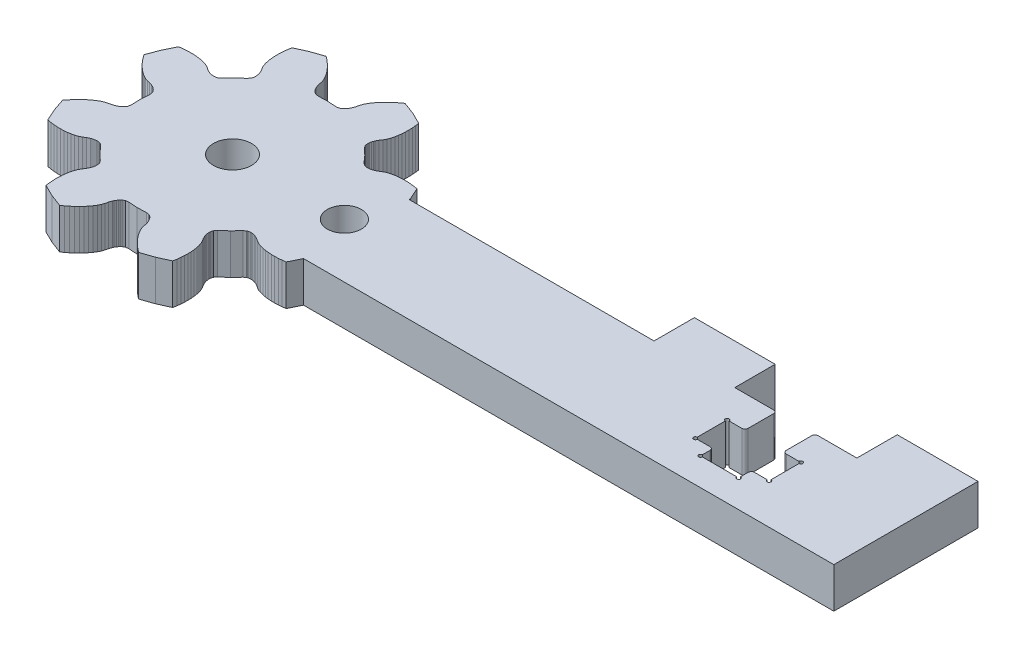
SolidWorks part; units mm, degrees
ref_plane "Front Plane" through (0, 0, 0) normal (0, 0, 1) x (1, 0, 0)
ref_plane "Top Plane" through (0, 0, 0) normal (0, 1, 0) x (1, 0, 0)
ref_plane "Right Plane" through (0, 0, 0) normal (1, 0, 0) x (0, 0, -1)
sketch "Sketch1" plane through (0, 0, 0) normal (0, 1, 0) x (1, 0, 0)
  line L0 (118.5341, 166.0961) -> (137.7907, 166.0961)
  line L1 (160.0907, 166.0961) -> (160.0907, 157.9324)
  line L2 (160.0907, 157.9324) -> (118.4045, 157.9258)
  line L3 (160.0907, 166.0961) -> (160.0907, 169.2711)
  line L4 (160.0907, 169.2711) -> (153.7407, 169.2711)
  line L5 (153.7407, 169.2711) -> (153.7407, 166.0961)
  line L6 (148.9407, 166.0961) -> (148.9407, 157.9306) construction
  line L7 (144.1407, 166.0961) -> (144.1407, 169.2711)
  line L8 (144.1407, 169.2711) -> (137.7907, 169.2711)
  line L9 (137.7907, 169.2711) -> (137.7907, 166.0961)
  line L10 (144.1407, 166.0961) -> (147.1907, 166.0961)
  line L11 (147.4407, 165.8461) -> (147.4407, 163.8461)
  line L12 (147.1907, 163.5961) -> (146.1907, 163.5961)
  line L13 (146.0407, 163.4461) -> (146.0407, 161.2461)
  line L14 (146.1907, 161.0961) -> (147.1907, 161.0961)
  line L15 (147.4407, 160.8461) -> (147.4407, 160.2461)
  line L16 (147.5907, 160.0961) -> (150.2907, 160.0961)
  line L17 (150.4407, 160.8461) -> (150.4407, 160.2461)
  line L18 (151.6907, 161.0961) -> (150.6907, 161.0961)
  line L19 (151.8407, 163.4461) -> (151.8407, 161.2461)
  line L20 (150.6907, 163.5961) -> (151.6907, 163.5961)
  line L21 (150.4407, 165.8461) -> (150.4407, 163.8461)
  line L22 (150.6907, 166.0961) -> (153.7407, 166.0961)
  line L1608 (118.5341, 166.0961) -> (118.5341, 166.193)
  line L1609 (118.5341, 166.193) -> (118.1081, 167.1345)
  line L1610 (118.1081, 167.1345) -> (117.8266, 167.1811)
  line L1611 (117.8266, 167.1811) -> (117.5494, 167.2141)
  line L1612 (117.5494, 167.2141) -> (117.277, 167.2336)
  line L1613 (117.277, 167.2336) -> (117.0101, 167.2392)
  line L1614 (117.0101, 167.2392) -> (116.7493, 167.2309)
  line L1615 (116.7493, 167.2309) -> (116.4956, 167.2082)
  line L1616 (116.4956, 167.2082) -> (116.2497, 167.1704)
  line L1617 (116.2497, 167.1704) -> (116.0133, 167.1164)
  line L1618 (116.0133, 167.1164) -> (115.7883, 167.0435)
  line L1619 (115.7883, 167.0435) -> (115.5824, 166.9415)
  line L1620 (115.5824, 166.9415) -> (115.3904, 166.8184)
  line L1621 (115.3904, 166.8184) -> (115.1836, 166.7174)
  line L1622 (115.1836, 166.7174) -> (115.0732, 166.6772)
  line L1623 (115.0732, 166.6772) -> (114.9567, 166.6456)
  line L1624 (114.9567, 166.6456) -> (114.8323, 166.6253)
  line L1625 (114.8323, 166.6253) -> (114.766, 166.6206)
  line L1626 (114.766, 166.6206) -> (114.696, 166.6208)
  line L1627 (114.696, 166.6208) -> (114.6211, 166.6276)
  line L1628 (114.6211, 166.6276) -> (114.5385, 166.6443)
  line L1629 (114.5385, 166.6443) -> (114.4416, 166.6792)
  line L1630 (114.4416, 166.6792) -> (114.2616, 166.8186)
  line L1631 (114.2616, 166.8186) -> (113.7953, 167.3484)
  line L1632 (113.7953, 167.3484) -> (113.2804, 167.8311)
  line L1633 (113.2804, 167.8311) -> (113.1468, 168.0154)
  line L1634 (113.1468, 168.0154) -> (113.1149, 168.1133)
  line L1635 (113.1149, 168.1133) -> (113.1008, 168.1964)
  line L1636 (113.1008, 168.1964) -> (113.0963, 168.2716)
  line L1637 (113.0963, 168.2716) -> (113.0983, 168.3415)
  line L1638 (113.0983, 168.3415) -> (113.1051, 168.4076)
  line L1639 (113.1051, 168.4076) -> (113.1293, 168.5313)
  line L1640 (113.1293, 168.5313) -> (113.1645, 168.6468)
  line L1641 (113.1645, 168.6468) -> (113.2082, 168.7559)
  line L1642 (113.2082, 168.7559) -> (113.3157, 168.9594)
  line L1643 (113.3157, 168.9594) -> (113.4447, 169.1474)
  line L1644 (113.4447, 169.1474) -> (113.5532, 169.35)
  line L1645 (113.5532, 169.35) -> (113.633, 169.5726)
  line L1646 (113.633, 169.5726) -> (113.6945, 169.8072)
  line L1647 (113.6945, 169.8072) -> (113.74, 170.0517)
  line L1648 (113.74, 170.0517) -> (113.7706, 170.3047)
  line L1649 (113.7706, 170.3047) -> (113.7871, 170.565)
  line L1650 (113.7871, 170.565) -> (113.7899, 170.832)
  line L1651 (113.7899, 170.832) -> (113.779, 171.1049)
  line L1652 (113.779, 171.1049) -> (113.7547, 171.383)
  line L1653 (113.7547, 171.383) -> (113.717, 171.6658)
  line L1654 (113.717, 171.6658) -> (112.7893, 172.1212)
  line L1655 (112.7893, 172.1212) -> (111.8223, 172.4857)
  line L1656 (111.8223, 172.4857) -> (111.5903, 172.3196)
  line L1657 (111.5903, 172.3196) -> (111.371, 172.1469)
  line L1658 (111.371, 172.1469) -> (111.1646, 171.9681)
  line L1659 (111.1646, 171.9681) -> (110.9718, 171.7833)
  line L1660 (110.9718, 171.7833) -> (110.7934, 171.593)
  line L1661 (110.7934, 171.593) -> (110.63, 171.3975)
  line L1662 (110.63, 171.3975) -> (110.4829, 171.197)
  line L1663 (110.4829, 171.197) -> (110.3539, 170.9916)
  line L1664 (110.3539, 170.9916) -> (110.2464, 170.781)
  line L1665 (110.2464, 170.781) -> (110.1728, 170.5633)
  line L1666 (110.1728, 170.5633) -> (110.1241, 170.3405)
  line L1667 (110.1241, 170.3405) -> (110.0493, 170.1228)
  line L1668 (110.0493, 170.1228) -> (109.9997, 170.0163)
  line L1669 (109.9997, 170.0163) -> (109.9397, 169.9116)
  line L1670 (109.9397, 169.9116) -> (109.8661, 169.8092)
  line L1671 (109.8661, 169.8092) -> (109.8225, 169.759)
  line L1672 (109.8225, 169.759) -> (109.7729, 169.7097)
  line L1673 (109.7729, 169.7097) -> (109.715, 169.6615)
  line L1674 (109.715, 169.6615) -> (109.6448, 169.615)
  line L1675 (109.6448, 169.615) -> (109.5516, 169.5712)
  line L1676 (109.5516, 169.5712) -> (109.3258, 169.5424)
  line L1677 (109.3258, 169.5424) -> (108.6215, 169.5873)
  line L1678 (108.6215, 169.5873) -> (107.9161, 169.5646)
  line L1679 (107.9161, 169.5646) -> (107.6912, 169.6004)
  line L1680 (107.6912, 169.6004) -> (107.5995, 169.6471)
  line L1681 (107.5995, 169.6471) -> (107.5307, 169.6959)
  line L1682 (107.5307, 169.6959) -> (107.4745, 169.7459)
  line L1683 (107.4745, 169.7459) -> (107.4264, 169.7967)
  line L1684 (107.4264, 169.7967) -> (107.3844, 169.8482)
  line L1685 (107.3844, 169.8482) -> (107.3141, 169.9529)
  line L1686 (107.3141, 169.9529) -> (107.2574, 170.0594)
  line L1687 (107.2574, 170.0594) -> (107.2111, 170.1674)
  line L1688 (107.2111, 170.1674) -> (107.1432, 170.3873)
  line L1689 (107.1432, 170.3873) -> (107.1015, 170.6115)
  line L1690 (107.1015, 170.6115) -> (107.0349, 170.8315)
  line L1691 (107.0349, 170.8315) -> (106.934, 171.0453)
  line L1692 (106.934, 171.0453) -> (106.8116, 171.2547)
  line L1693 (106.8116, 171.2547) -> (106.6708, 171.4597)
  line L1694 (106.6708, 171.4597) -> (106.5136, 171.6603)
  line L1695 (106.5136, 171.6603) -> (106.3412, 171.856)
  line L1696 (106.3412, 171.856) -> (106.1543, 172.0467)
  line L1697 (106.1543, 172.0467) -> (105.9537, 172.232)
  line L1698 (105.9537, 172.232) -> (105.7399, 172.4115)
  line L1699 (105.7399, 172.4115) -> (105.5133, 172.5848)
  line L1700 (105.5133, 172.5848) -> (104.5353, 172.2508)
  line L1701 (104.5353, 172.2508) -> (103.5937, 171.8248)
  line L1702 (103.5937, 171.8248) -> (103.5472, 171.5433)
  line L1703 (103.5472, 171.5433) -> (103.5141, 171.2661)
  line L1704 (103.5141, 171.2661) -> (103.4947, 170.9937)
  line L1705 (103.4947, 170.9937) -> (103.489, 170.7268)
  line L1706 (103.489, 170.7268) -> (103.4974, 170.4661)
  line L1707 (103.4974, 170.4661) -> (103.52, 170.2122)
  line L1708 (103.52, 170.2122) -> (103.5578, 169.9665)
  line L1709 (103.5578, 169.9665) -> (103.6119, 169.73)
  line L1710 (103.6119, 169.73) -> (103.6847, 169.5051)
  line L1711 (103.6847, 169.5051) -> (103.7867, 169.2991)
  line L1712 (103.7867, 169.2991) -> (103.9099, 169.1071)
  line L1713 (103.9099, 169.1071) -> (104.0108, 168.9003)
  line L1714 (104.0108, 168.9003) -> (104.0511, 168.7899)
  line L1715 (104.0511, 168.7899) -> (104.0826, 168.6735)
  line L1716 (104.0826, 168.6735) -> (104.103, 168.549)
  line L1717 (104.103, 168.549) -> (104.1077, 168.4827)
  line L1718 (104.1077, 168.4827) -> (104.1075, 168.4127)
  line L1719 (104.1075, 168.4127) -> (104.1006, 168.3378)
  line L1720 (104.1006, 168.3378) -> (104.0839, 168.2552)
  line L1721 (104.0839, 168.2552) -> (104.049, 168.1583)
  line L1722 (104.049, 168.1583) -> (103.9096, 167.9783)
  line L1723 (103.9096, 167.9783) -> (103.3799, 167.512)
  line L1724 (103.3799, 167.512) -> (102.8972, 166.9971)
  line L1725 (102.8972, 166.9971) -> (102.7129, 166.8635)
  line L1726 (102.7129, 166.8635) -> (102.6149, 166.8316)
  line L1727 (102.6149, 166.8316) -> (102.5318, 166.8175)
  line L1728 (102.5318, 166.8175) -> (102.4567, 166.8131)
  line L1729 (102.4567, 166.8131) -> (102.3868, 166.815)
  line L1730 (102.3868, 166.815) -> (102.3207, 166.8218)
  line L1731 (102.3207, 166.8218) -> (102.1969, 166.8461)
  line L1732 (102.1969, 166.8461) -> (102.0815, 166.8813)
  line L1733 (102.0815, 166.8813) -> (101.9724, 166.9249)
  line L1734 (101.9724, 166.9249) -> (101.7689, 167.0324)
  line L1735 (101.7689, 167.0324) -> (101.5809, 167.1615)
  line L1736 (101.5809, 167.1615) -> (101.3782, 167.2699)
  line L1737 (101.3782, 167.2699) -> (101.1557, 167.3498)
  line L1738 (101.1557, 167.3498) -> (100.921, 167.4112)
  line L1739 (100.921, 167.4112) -> (100.6765, 167.4567)
  line L1740 (100.6765, 167.4567) -> (100.4236, 167.4874)
  line L1741 (100.4236, 167.4874) -> (100.1632, 167.5039)
  line L1742 (100.1632, 167.5039) -> (99.8963, 167.5066)
  line L1743 (99.8963, 167.5066) -> (99.6234, 167.4957)
  line L1744 (99.6234, 167.4957) -> (99.3453, 167.4714)
  line L1745 (99.3453, 167.4714) -> (99.0625, 167.4337)
  line L1746 (99.0625, 167.4337) -> (98.6071, 166.506)
  line L1747 (98.6071, 166.506) -> (98.2426, 165.539)
  line L1748 (98.2426, 165.539) -> (98.4087, 165.3071)
  line L1749 (98.4087, 165.3071) -> (98.5813, 165.0877)
  line L1750 (98.5813, 165.0877) -> (98.7602, 164.8813)
  line L1751 (98.7602, 164.8813) -> (98.9449, 164.6886)
  line L1752 (98.9449, 164.6886) -> (99.1352, 164.5101)
  line L1753 (99.1352, 164.5101) -> (99.3307, 164.3467)
  line L1754 (99.3307, 164.3467) -> (99.5312, 164.1996)
  line L1755 (99.5312, 164.1996) -> (99.7367, 164.0706)
  line L1756 (99.7367, 164.0706) -> (99.9472, 163.9631)
  line L1757 (99.9472, 163.9631) -> (100.165, 163.8895)
  line L1758 (100.165, 163.8895) -> (100.3878, 163.8409)
  line L1759 (100.3878, 163.8409) -> (100.6054, 163.7661)
  line L1760 (100.6054, 163.7661) -> (100.7119, 163.7165)
  line L1761 (100.7119, 163.7165) -> (100.8166, 163.6564)
  line L1762 (100.8166, 163.6564) -> (100.919, 163.5828)
  line L1763 (100.919, 163.5828) -> (100.9692, 163.5392)
  line L1764 (100.9692, 163.5392) -> (101.0185, 163.4896)
  line L1765 (101.0185, 163.4896) -> (101.0667, 163.4318)
  line L1766 (101.0667, 163.4318) -> (101.1133, 163.3615)
  line L1767 (101.1133, 163.3615) -> (101.1571, 163.2683)
  line L1768 (101.1571, 163.2683) -> (101.1858, 163.0425)
  line L1769 (101.1858, 163.0425) -> (101.1409, 162.3382)
  line L1770 (101.1409, 162.3382) -> (101.1637, 161.6328)
  line L1771 (101.1637, 161.6328) -> (101.1279, 161.408)
  line L1772 (101.1279, 161.408) -> (101.0812, 161.3162)
  line L1773 (101.0812, 161.3162) -> (101.0324, 161.2475)
  line L1774 (101.0324, 161.2475) -> (100.9824, 161.1912)
  line L1775 (100.9824, 161.1912) -> (100.9316, 161.1431)
  line L1776 (100.9316, 161.1431) -> (100.88, 161.1012)
  line L1777 (100.88, 161.1012) -> (100.7753, 161.0308)
  line L1778 (100.7753, 161.0308) -> (100.6689, 160.9741)
  line L1779 (100.6689, 160.9741) -> (100.5608, 160.9278)
  line L1780 (100.5608, 160.9278) -> (100.341, 160.8599)
  line L1781 (100.341, 160.8599) -> (100.1167, 160.8183)
  line L1782 (100.1167, 160.8183) -> (99.8968, 160.7516)
  line L1783 (99.8968, 160.7516) -> (99.6829, 160.6507)
  line L1784 (99.6829, 160.6507) -> (99.4736, 160.5283)
  line L1785 (99.4736, 160.5283) -> (99.2685, 160.3876)
  line L1786 (99.2685, 160.3876) -> (99.068, 160.2304)
  line L1787 (99.068, 160.2304) -> (98.8722, 160.0579)
  line L1788 (98.8722, 160.0579) -> (98.6815, 159.8711)
  line L1789 (98.6815, 159.8711) -> (98.4962, 159.6704)
  line L1790 (98.4962, 159.6704) -> (98.3167, 159.4566)
  line L1791 (98.3167, 159.4566) -> (98.1435, 159.23)
  line L1792 (98.1435, 159.23) -> (98.4774, 158.252)
  line L1793 (98.4774, 158.252) -> (98.9034, 157.3104)
  line L1794 (98.9034, 157.3104) -> (99.1849, 157.2639)
  line L1795 (99.1849, 157.2639) -> (99.4621, 157.2308)
  line L1796 (99.4621, 157.2308) -> (99.7345, 157.2114)
  line L1797 (99.7345, 157.2114) -> (100.0015, 157.2058)
  line L1798 (100.0015, 157.2058) -> (100.2622, 157.2141)
  line L1799 (100.2622, 157.2141) -> (100.516, 157.2368)
  line L1800 (100.516, 157.2368) -> (100.7618, 157.2745)
  line L1801 (100.7618, 157.2745) -> (100.9983, 157.3286)
  line L1802 (100.9983, 157.3286) -> (101.2232, 157.4015)
  line L1803 (101.2232, 157.4015) -> (101.4292, 157.5035)
  line L1804 (101.4292, 157.5035) -> (101.6211, 157.6266)
  line L1805 (101.6211, 157.6266) -> (101.8279, 157.7276)
  line L1806 (101.8279, 157.7276) -> (101.9383, 157.7678)
  line L1807 (101.9383, 157.7678) -> (102.0548, 157.7994)
  line L1808 (102.0548, 157.7994) -> (102.1793, 157.8197)
  line L1809 (102.1793, 157.8197) -> (102.2455, 157.8244)
  line L1810 (102.2455, 157.8244) -> (102.3155, 157.8242)
  line L1811 (102.3155, 157.8242) -> (102.3905, 157.8174)
  line L1812 (102.3905, 157.8174) -> (102.4731, 157.8007)
  line L1813 (102.4731, 157.8007) -> (102.5699, 157.7657)
  line L1814 (102.5699, 157.7657) -> (102.7499, 157.6264)
  line L1815 (102.7499, 157.6264) -> (103.2163, 157.0966)
  line L1816 (103.2163, 157.0966) -> (103.7311, 156.6139)
  line L1817 (103.7311, 156.6139) -> (103.8648, 156.4296)
  line L1818 (103.8648, 156.4296) -> (103.8966, 156.3317)
  line L1819 (103.8966, 156.3317) -> (103.9107, 156.2486)
  line L1820 (103.9107, 156.2486) -> (103.9152, 156.1734)
  line L1821 (103.9152, 156.1734) -> (103.9132, 156.1035)
  line L1822 (103.9132, 156.1035) -> (103.9065, 156.0374)
  line L1823 (103.9065, 156.0374) -> (103.8822, 155.9136)
  line L1824 (103.8822, 155.9136) -> (103.847, 155.7982)
  line L1825 (103.847, 155.7982) -> (103.8033, 155.6891)
  line L1826 (103.8033, 155.6891) -> (103.6959, 155.4856)
  line L1827 (103.6959, 155.4856) -> (103.5668, 155.2976)
  line L1828 (103.5668, 155.2976) -> (103.4584, 155.0949)
  line L1829 (103.4584, 155.0949) -> (103.3785, 154.8724)
  line L1830 (103.3785, 154.8724) -> (103.317, 154.6378)
  line L1831 (103.317, 154.6378) -> (103.2715, 154.3933)
  line L1832 (103.2715, 154.3933) -> (103.2409, 154.1403)
  line L1833 (103.2409, 154.1403) -> (103.2244, 153.8799)
  line L1834 (103.2244, 153.8799) -> (103.2217, 153.613)
  line L1835 (103.2217, 153.613) -> (103.2325, 153.3401)
  line L1836 (103.2325, 153.3401) -> (103.2568, 153.062)
  line L1837 (103.2568, 153.062) -> (103.2945, 152.7792)
  line L1838 (103.2945, 152.7792) -> (104.2222, 152.3238)
  line L1839 (104.2222, 152.3238) -> (105.1892, 151.9593)
  line L1840 (105.1892, 151.9593) -> (105.4212, 152.1254)
  line L1841 (105.4212, 152.1254) -> (105.6406, 152.298)
  line L1842 (105.6406, 152.298) -> (105.8469, 152.4769)
  line L1843 (105.8469, 152.4769) -> (106.0397, 152.6617)
  line L1844 (106.0397, 152.6617) -> (106.2182, 152.8519)
  line L1845 (106.2182, 152.8519) -> (106.3816, 153.0474)
  line L1846 (106.3816, 153.0474) -> (106.5287, 153.248)
  line L1847 (106.5287, 153.248) -> (106.6576, 153.4534)
  line L1848 (106.6576, 153.4534) -> (106.7652, 153.6639)
  line L1849 (106.7652, 153.6639) -> (106.8387, 153.8817)
  line L1850 (106.8387, 153.8817) -> (106.8874, 154.1045)
  line L1851 (106.8874, 154.1045) -> (106.9622, 154.3221)
  line L1852 (106.9622, 154.3221) -> (107.0118, 154.4286)
  line L1853 (107.0118, 154.4286) -> (107.0719, 154.5333)
  line L1854 (107.0719, 154.5333) -> (107.1455, 154.6358)
  line L1855 (107.1455, 154.6358) -> (107.189, 154.6859)
  line L1856 (107.189, 154.6859) -> (107.2386, 154.7352)
  line L1857 (107.2386, 154.7352) -> (107.2965, 154.7834)
  line L1858 (107.2965, 154.7834) -> (107.3667, 154.83)
  line L1859 (107.3667, 154.83) -> (107.4599, 154.8738)
  line L1860 (107.4599, 154.8738) -> (107.6857, 154.9026)
  line L1861 (107.6857, 154.9026) -> (108.3901, 154.8577)
  line L1862 (108.3901, 154.8577) -> (109.0955, 154.8804)
  line L1863 (109.0955, 154.8804) -> (109.3203, 154.8446)
  line L1864 (109.3203, 154.8446) -> (109.4121, 154.7979)
  line L1865 (109.4121, 154.7979) -> (109.4808, 154.7491)
  line L1866 (109.4808, 154.7491) -> (109.5371, 154.6991)
  line L1867 (109.5371, 154.6991) -> (109.5851, 154.6483)
  line L1868 (109.5851, 154.6483) -> (109.6271, 154.5968)
  line L1869 (109.6271, 154.5968) -> (109.6974, 154.4921)
  line L1870 (109.6974, 154.4921) -> (109.7542, 154.3856)
  line L1871 (109.7542, 154.3856) -> (109.8004, 154.2775)
  line L1872 (109.8004, 154.2775) -> (109.8684, 154.0577)
  line L1873 (109.8684, 154.0577) -> (109.91, 153.8335)
  line L1874 (109.91, 153.8335) -> (109.9767, 153.6135)
  line L1875 (109.9767, 153.6135) -> (110.0775, 153.3997)
  line L1876 (110.0775, 153.3997) -> (110.2, 153.1903)
  line L1877 (110.2, 153.1903) -> (110.3407, 152.9852)
  line L1878 (110.3407, 152.9852) -> (110.4979, 152.7847)
  line L1879 (110.4979, 152.7847) -> (110.6703, 152.5889)
  line L1880 (110.6703, 152.5889) -> (110.8572, 152.3982)
  line L1881 (110.8572, 152.3982) -> (111.0578, 152.213)
  line L1882 (111.0578, 152.213) -> (111.2717, 152.0335)
  line L1883 (111.2717, 152.0335) -> (111.4983, 151.8602)
  line L1884 (111.4983, 151.8602) -> (112.4763, 152.1941)
  line L1885 (112.4763, 152.1941) -> (113.4178, 152.6202)
  line L1886 (113.4178, 152.6202) -> (113.4644, 152.9016)
  line L1887 (113.4644, 152.9016) -> (113.4974, 153.1789)
  line L1888 (113.4974, 153.1789) -> (113.5168, 153.4513)
  line L1889 (113.5168, 153.4513) -> (113.5225, 153.7182)
  line L1890 (113.5225, 153.7182) -> (113.5142, 153.9789)
  line L1891 (113.5142, 153.9789) -> (113.4915, 154.2327)
  line L1892 (113.4915, 154.2327) -> (113.4537, 154.4785)
  line L1893 (113.4537, 154.4785) -> (113.3996, 154.715)
  line L1894 (113.3996, 154.715) -> (113.3268, 154.9399)
  line L1895 (113.3268, 154.9399) -> (113.2248, 155.1459)
  line L1896 (113.2248, 155.1459) -> (113.1017, 155.3378)
  line L1897 (113.1017, 155.3378) -> (113.0007, 155.5446)
  line L1898 (113.0007, 155.5446) -> (112.9604, 155.655)
  line L1899 (112.9604, 155.655) -> (112.9289, 155.7715)
  line L1900 (112.9289, 155.7715) -> (112.9085, 155.896)
  line L1901 (112.9085, 155.896) -> (112.9038, 155.9623)
  line L1902 (112.9038, 155.9623) -> (112.9041, 156.0322)
  line L1903 (112.9041, 156.0322) -> (112.9109, 156.1072)
  line L1904 (112.9109, 156.1072) -> (112.9276, 156.1898)
  line L1905 (112.9276, 156.1898) -> (112.9625, 156.2866)
  line L1906 (112.9625, 156.2866) -> (113.1019, 156.4667)
  line L1907 (113.1019, 156.4667) -> (113.6316, 156.933)
  line L1908 (113.6316, 156.933) -> (114.1144, 157.4478)
  line L1909 (114.1144, 157.4478) -> (114.2987, 157.5815)
  line L1910 (114.2987, 157.5815) -> (114.3966, 157.6133)
  line L1911 (114.3966, 157.6133) -> (114.4797, 157.6275)
  line L1912 (114.4797, 157.6275) -> (114.5548, 157.6319)
  line L1913 (114.5548, 157.6319) -> (114.6247, 157.63)
  line L1914 (114.6247, 157.63) -> (114.6908, 157.6232)
  line L1915 (114.6908, 157.6232) -> (114.8146, 157.5989)
  line L1916 (114.8146, 157.5989) -> (114.9301, 157.5637)
  line L1917 (114.9301, 157.5637) -> (115.0392, 157.52)
  line L1918 (115.0392, 157.52) -> (115.2426, 157.4126)
  line L1919 (115.2426, 157.4126) -> (115.4307, 157.2835)
  line L1920 (115.4307, 157.2835) -> (115.6333, 157.1751)
  line L1921 (115.6333, 157.1751) -> (115.8558, 157.0952)
  line L1922 (115.8558, 157.0952) -> (116.0905, 157.0337)
  line L1923 (116.0905, 157.0337) -> (116.335, 156.9883)
  line L1924 (116.335, 156.9883) -> (116.5879, 156.9576)
  line L1925 (116.5879, 156.9576) -> (116.8483, 156.9411)
  line L1926 (116.8483, 156.9411) -> (117.1153, 156.9384)
  line L1927 (117.1153, 156.9384) -> (117.3881, 156.9492)
  line L1928 (117.3881, 156.9492) -> (117.6663, 156.9736)
  line L1929 (117.6663, 156.9736) -> (117.949, 157.0112)
  line L1930 (117.949, 157.0112) -> (118.4045, 157.9389)
  line L1931 (118.4045, 157.9389) -> (118.4045, 157.9258)
  circle A0 centre (108.5161, 162.2225) radius 1.5
  circle A1 centre (117.3319, 162.206) radius 1.3413
  arc A2 (146.0407, 161.2461) -> (146.1907, 161.0961) centre (146.0407, 161.0961) ccw
  arc A3 (146.1907, 163.5961) -> (146.0407, 163.4461) centre (146.0407, 163.5961) ccw
  arc A4 (147.4407, 160.2461) -> (147.5907, 160.0961) centre (147.4407, 160.0961) ccw
  arc A5 (147.1907, 161.0961) -> (147.4407, 160.8461) centre (147.1907, 160.8461) cw
  arc A6 (147.4407, 163.8461) -> (147.1907, 163.5961) centre (147.1907, 163.8461) cw
  arc A7 (150.4407, 163.8461) -> (150.6907, 163.5961) centre (150.6907, 163.8461) ccw
  arc A8 (150.6907, 161.0961) -> (150.4407, 160.8461) centre (150.6907, 160.8461) ccw
  arc A9 (150.4407, 160.2461) -> (150.2907, 160.0961) centre (150.4407, 160.0961) cw
  arc A10 (151.6907, 163.5961) -> (151.8407, 163.4461) centre (151.8407, 163.5961) cw
  arc A11 (151.8407, 161.2461) -> (151.6907, 161.0961) centre (151.8407, 161.0961) cw
  arc A12 (150.4407, 165.8461) -> (150.6907, 166.0961) centre (150.6907, 165.8461) cw
  arc A13 (147.4407, 165.8461) -> (147.1907, 166.0961) centre (147.1907, 165.8461) ccw
  point P30 (147.4407, 161.0961)
  point P33 (147.4407, 163.5961)
  point P49 (148.9407, 160.0961)
  point P50 (150.4407, 163.5961)
  point P51 (150.4407, 161.0961)
  point P54 (150.4407, 166.0961)
  point P57 (147.4407, 166.0961)
  dimension "D12" = 0.3
  dimension "D13" = 0.3
  dimension "D14" = 0.3
  dimension "D15" = 0.25
  dimension "D16" = 0.25
  dimension "D1" = 3.175
  dimension "D2" = 3.175
  dimension "D3" = 6.35
  dimension "D4" = 6.35
  dimension "D5" = 9.6
  dimension "D6" = 1
  dimension "D7" = 2.5
  dimension "D8" = 2.5
  dimension "D9" = 2.9
  dimension "D10" = 1.5
  dimension "D11" = 1.5
extrude "Boss-Extrude1" add sketch "Sketch1" along normal blind 3.175
